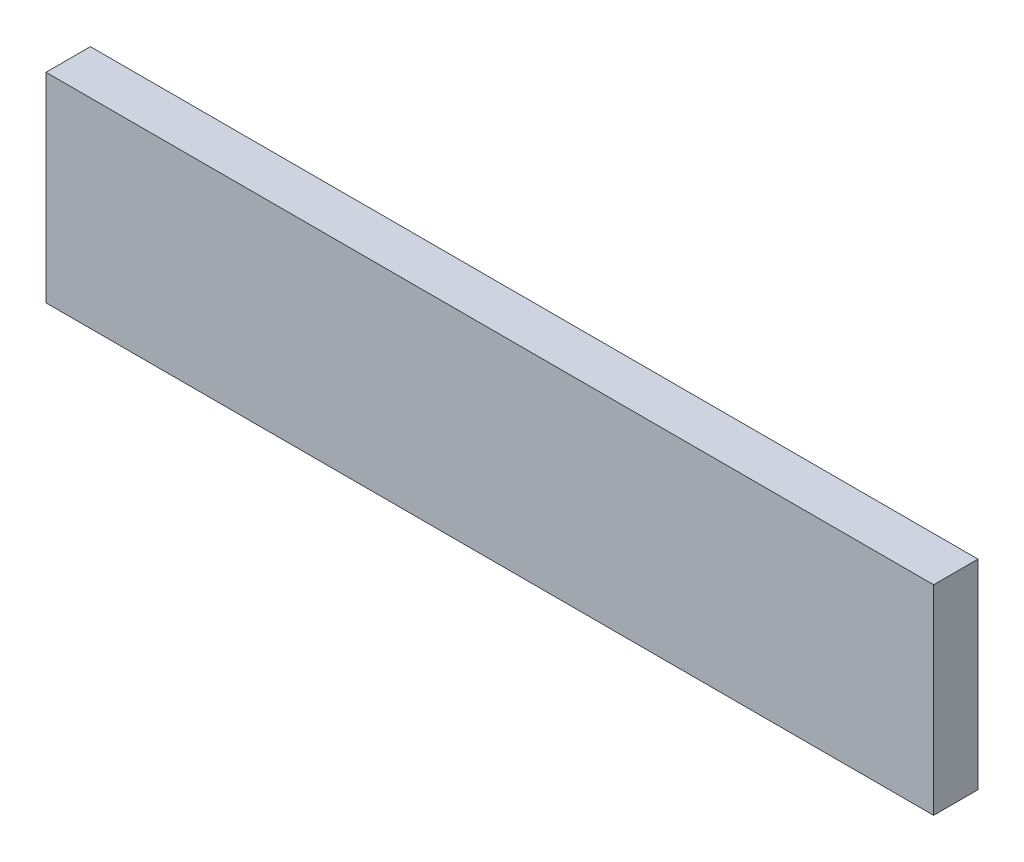
SolidWorks part; units mm, degrees
ref_plane "Plan de face" through (0, 0, 0) normal (0, 0, 1) x (1, 0, 0)
ref_plane "Plan de dessus" through (0, 0, 0) normal (0, 1, 0) x (1, 0, 0)
ref_plane "Plan de droite" through (0, 0, 0) normal (1, 0, 0) x (0, 0, -1)
sketch "Esquisse1" plane through (0, 0, 0) normal (0, 0, 1) x (1, 0, 0)
  line L1 (-123.6211, 34.7998) -> (276.3789, 34.7998)
  line L2 (-123.6211, 34.7998) -> (-123.6211, -55.2002)
  line L3 (-123.6211, -55.2002) -> (276.3789, -55.2002)
  line L4 (276.3789, 34.7998) -> (276.3789, -55.2002)
  dimension "D1" = 400
  dimension "D2" = 90
extrude "Boss.-Extru.1" add sketch "Esquisse1" along normal blind 20
